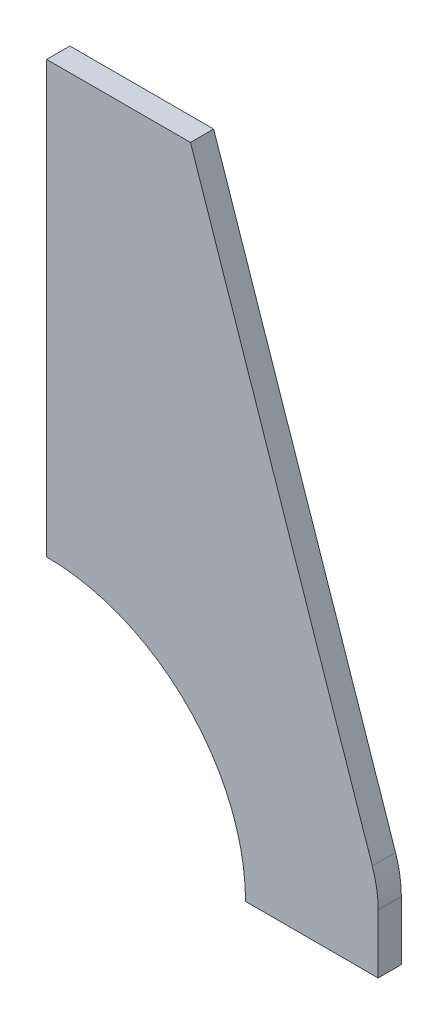
SolidWorks part; units mm, degrees
ref_plane "Front Plane" through (0, 0, 0) normal (0, 0, 1) x (1, 0, 0)
ref_plane "Top Plane" through (0, 0, 0) normal (0, 1, 0) x (1, 0, 0)
ref_plane "Right Plane" through (0, 0, 0) normal (1, 0, 0) x (0, 0, -1)
sketch "Sketch1" plane through (0, 0, 0) normal (0, 0, 1) x (1, 0, 0)
  line L0 (-100, 0) -> (100, 0)
  line L1 (-100, 0) -> (-100, 23.2527)
  line L2 (-100, 23.2527) -> (-26.9482, 238.3913)
  line L3 (-26.9482, 238.3913) -> (0, 238.3913) construction
  line L4 (0, 238.3913) -> (26.9482, 238.3913) construction
  line L5 (26.9482, 238.3913) -> (100, 23.2527)
  line L6 (100, 23.2527) -> (100, 0)
  line L7 (0, 238.3913) -> (0, 0) construction
  line L8 (0, 215) -> (56.5878, 215) construction
  line L13 (-26.9482, 238.3913) -> (-24.9482, 238.3913)
  line L15 (26.9482, 238.3913) -> (24.9482, 238.3913)
  arc A2 (-24.9482, 238.3913) -> (24.9482, 238.3913) centre (0, 240) ccw
  point P4 (0, 0)
  dimension "D2" = 50
  dimension "D1" = 215
  dimension "D3" = 200
  dimension "D4" = 2
extrude "Boss-Extrude1" add sketch "Sketch1" along normal blind 7
fillet "Fillet1" radius 33 2 edges at (-100, 23.2527, 3.5) (100, 23.2527, 3.5)
sketch "Sketch2" plane through (0, 0, 7) normal (0, 0, 1) x (1, 0, 0)
  circle A0 centre (0, 0) radius 60
  dimension "D1" = 120
extrude "Cut-Extrude1" cut sketch "Sketch2" against normal through all
sketch "Sketch3" plane through (0, 0, 0) normal (1, 0, 0) x (0, 0, -1)
  line L1 (-93.2456, 348.5248) -> (87.7985, 348.5248)
  line L2 (-93.2456, 348.5248) -> (-93.2456, -132.2638)
  line L3 (-93.2456, -132.2638) -> (87.7985, -132.2638)
  line L4 (87.7985, 348.5248) -> (87.7985, -132.2638)
  line L5 (-93.2456, 348.5248) -> (87.7985, -132.2638) construction
  line L6 (-93.2456, -132.2638) -> (87.7985, 348.5248) construction
  point P0 (-2.7235, 108.1305)
extrude "Cut-Extrude2" cut sketch "Sketch3" against normal through all
ref_plane "Plane1" through (0, 0, 3.5) normal (0, 0, 1) x (1, 0, 0)
ref_plane "Plane2" [suppressed] through (0, 0, 0) normal (1, 0, 0) x (0, 0, -1)
ref_plane "Plane3" through (0, 190, 0) normal (0, 1, 0) x (1, 0, 0)
sketch "Sketch4" plane through (0, 190, 0) normal (0, 1, 0) x (1, 0, 0)
  line L1 (-39.1885, 27.5446) -> (130.5805, 27.5446)
  line L2 (-39.1885, 27.5446) -> (-39.1885, -21.5529)
  line L3 (-39.1885, -21.5529) -> (130.5805, -21.5529)
  line L4 (130.5805, 27.5446) -> (130.5805, -21.5529)
  line L5 (-39.1885, 27.5446) -> (130.5805, -21.5529) construction
  line L6 (-39.1885, -21.5529) -> (130.5805, 27.5446) construction
  point P0 (45.696, 2.9959)
extrude "Cut-Extrude3" cut sketch "Sketch4" along normal through all
